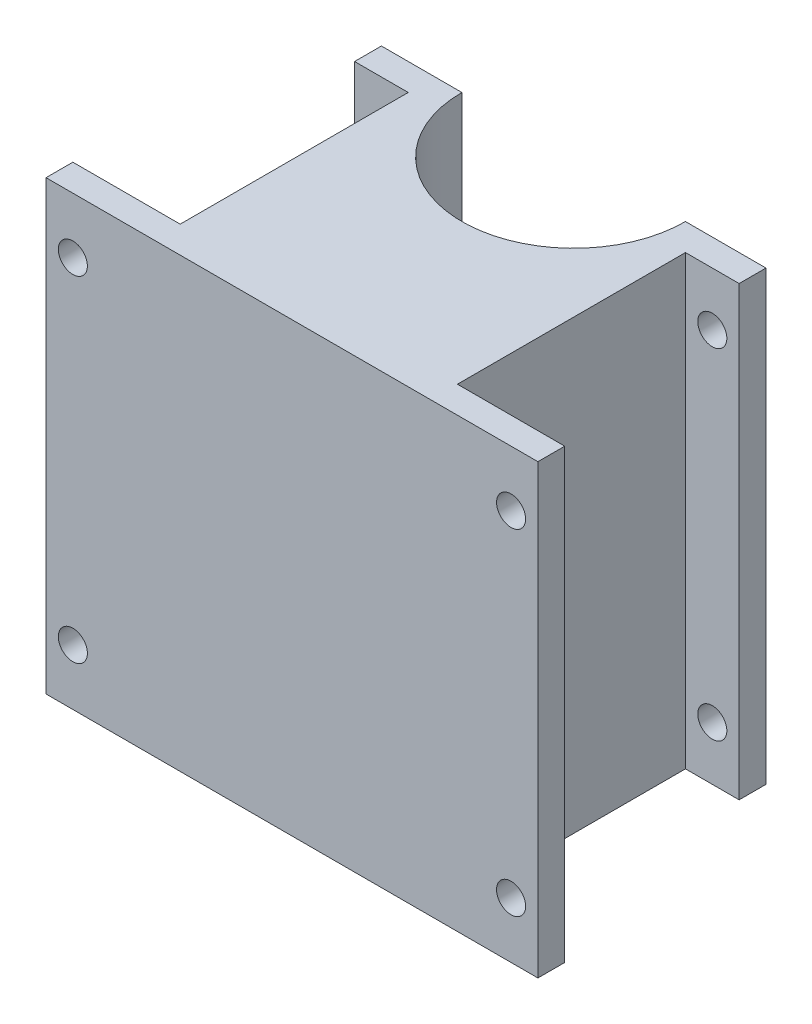
SolidWorks part; units mm, degrees
ref_plane "Plan de face" through (0, 0, 0) normal (0, 0, 1) x (1, 0, 0)
ref_plane "Plan de dessus" through (0, 0, 0) normal (0, 1, 0) x (1, 0, 0)
ref_plane "Plan de droite" through (0, 0, 0) normal (1, 0, 0) x (0, 0, -1)
sketch "Esquisse1" plane through (0, 0, 0) normal (0, 1, 0) x (1, 0, 0)
  line L5 (-6, 28.5) -> (-6, 31.5)
  line L6 (-6, 31.5) -> (3, 31.5)
  line L7 (37, 28.5) -> (37, 31.5)
  line L8 (37, 31.5) -> (28, 31.5)
  line L9 (-12, 3) -> (-12, 0)
  line L10 (-6, 28.5) -> (0, 28.5)
  line L11 (0, 28.5) -> (0, 3)
  line L12 (0, 3) -> (-12, 3)
  line L13 (-12, 0) -> (43, 0)
  line L14 (43, 0) -> (43, 3)
  line L15 (43, 3) -> (31, 3)
  line L16 (31, 3) -> (31, 28.5)
  line L17 (31, 28.5) -> (37, 28.5)
  line L18 (15.5, 0) -> (15.5, 31.5) construction
  arc A0 (3, 31.5) -> (28, 31.5) centre (15.5, 31.5) ccw
  dimension "D1" = 6
  dimension "D2" = 25.5
  dimension "D3" = 25
  dimension "D4" = 3
  dimension "D5" = 3
  dimension "D6" = 3
  dimension "D7" = 9
  dimension "D8" = 9
  dimension "D9" = 3
  dimension "D10" = 25.5
  dimension "D11" = 6
  dimension "D12" = 12
  dimension "D13" = 12
  dimension "D14" = 31.5
extrude "Boss.-Extru.2" add sketch "Esquisse1" along normal blind 50
sketch "Esquisse2" plane through (0, 0, -31.5) normal (0, 0, -1) x (-1, 0, 0)
  line L0 (-37, 50) -> (-37, 0) construction
  line L4 (6, 50) -> (6, 0) construction
  line L6 (-32.5, 50) -> (-32.5, 0) construction
  line L9 (-37, 50) -> (-28, 50) construction
  line L10 (-37, 0) -> (-28, 0) construction
  line L11 (1.5, 50) -> (1.5, 0) construction
  line L12 (-3, 50) -> (6, 50) construction
  line L13 (-3, 0) -> (6, 0) construction
  circle A0 centre (3, 44) radius 1.625
  circle A1 centre (3, 6) radius 1.625
  circle A2 centre (-34, 44) radius 1.625
  circle A3 centre (-34, 6) radius 1.625
  dimension "D3" = 3.25
  dimension "D4" = 3.25
  dimension "D5" = 3.25
  dimension "D6" = 3.25
  dimension "D2" = 3
  dimension "D7" = 3
  dimension "D8" = 3
  dimension "D9" = 6
  dimension "D10" = 3
  dimension "D11" = 6
  dimension "D12" = 6
  dimension "D13" = 6
extrude "Enlèv. mat.-Extru.2" cut sketch "Esquisse2" against normal blind 6
sketch "Esquisse3" plane through (0, 0, -3) normal (0, 0, -1) x (-1, 0, 0)
  line L0 (-43, 0) -> (-31, 0) construction
  line L1 (-43, 50) -> (-43, 0) construction
  line L2 (-43, 50) -> (-31, 50) construction
  circle A0 centre (-40, 6.25) radius 1.625
  circle A1 centre (-40, 43.75) radius 1.625
  dimension "D1" = 3.25
  dimension "D2" = 6.25
  dimension "D3" = 3
  dimension "D4" = 6.25
  dimension "D5" = 3
sketch "Esquisse4" plane through (0, 0, -3) normal (0, 0, -1) x (-1, 0, 0)
  line L0 (12, 50) -> (12, 0) construction
  line L1 (0, 0) -> (12, 0) construction
  line L2 (0, 50) -> (12, 50) construction
  circle A0 centre (9, 6.25) radius 1.625
  circle A1 centre (9, 43.75) radius 1.625
  dimension "D1" = 3.25
  dimension "D6" = 3.25
  dimension "D2" = 3
  dimension "D3" = 6.25
  dimension "D4" = 6.25
  dimension "D5" = 3
extrude "Enlèv. mat.-Extru.3" cut sketch "Esquisse4" against normal blind 14
extrude "Enlèv. mat.-Extru.4" cut sketch "Esquisse3" against normal blind 14
